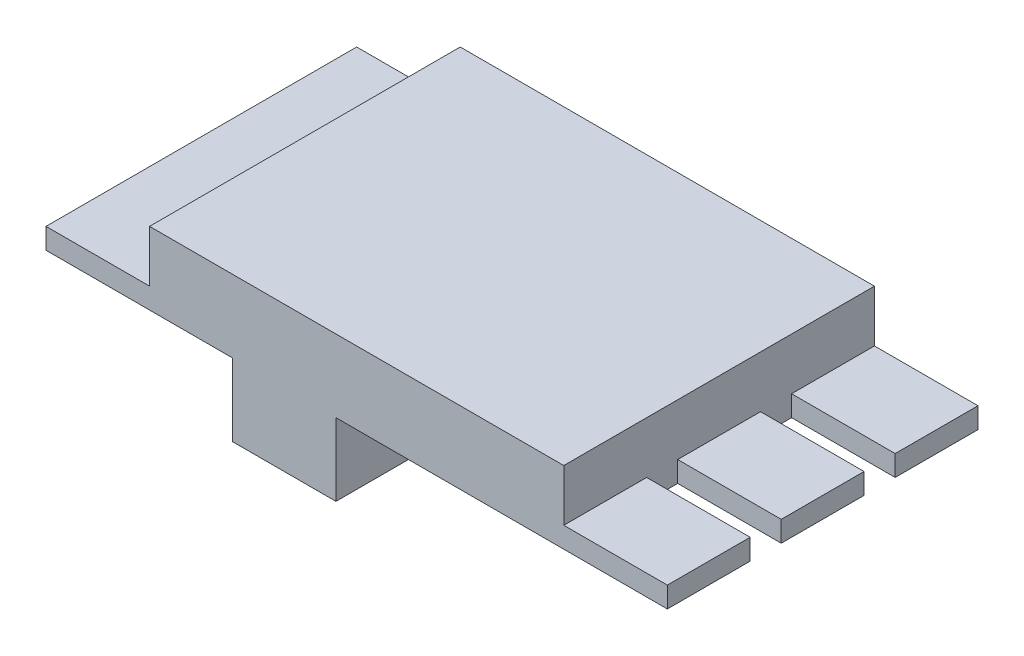
SolidWorks part; units mm, degrees
ref_plane "Front Plane" through (0, 0, 0) normal (0, 0, 1) x (1, 0, 0)
ref_plane "Top Plane" through (0, 0, 0) normal (0, 1, 0) x (1, 0, 0)
ref_plane "Right Plane" through (0, 0, 0) normal (1, 0, 0) x (0, 0, -1)
sketch "Sketch1" plane through (0, 0, 0) normal (0, 1, 0) x (1, 0, 0)
  line L1 (-15, -7.5) -> (15, -7.5)
  line L2 (-15, -7.5) -> (-15, 7.5)
  line L3 (-15, 7.5) -> (15, 7.5)
  line L4 (15, -7.5) -> (15, 7.5)
  line L5 (-15, -7.5) -> (15, 7.5) construction
  line L6 (-15, 7.5) -> (15, -7.5) construction
  point P0 (0, 0)
  dimension "D1" = 30
  dimension "D2" = 15
extrude "Boss-Extrude1" add sketch "Sketch1" along normal blind 7
sketch "Sketch2" plane through (0, 0, 7.5) normal (0, 0, 1) x (1, 0, 0)
  line L0 (15, 4.5) -> (10, 4.5)
  line L1 (15, 7) -> (15, 0) construction
  line L2 (10, 4.5) -> (10, 7)
  line L3 (-15, 7) -> (15, 7) construction
  line L4 (10, 7) -> (-10, 7)
  line L7 (-6, 3.5) -> (-6, 0)
  line L18 (15, 4.5) -> (15, 3.5)
  line L20 (-10, 7) -> (-10, 4.5)
  line L21 (-10, 4.5) -> (-15, 4.5)
  line L22 (-15, 7) -> (-15, 0) construction
  line L23 (-15, 4.5) -> (-15, 3.5)
  line L24 (-15, 3.5) -> (-6, 3.5)
  line L25 (-15, 0) -> (15, 0) construction
  line L26 (-6, 0) -> (-1, 0)
  line L27 (-1, 0) -> (-1, 3.5)
  line L28 (-1, 3.5) -> (15, 3.5)
  dimension "D1" = 5
  dimension "D2" = 20
  dimension "D3" = 5
  dimension "D4" = 1
  dimension "D5" = 16
  dimension "D7" = 1
sketch "Sketch3" plane through (0, 0, 7.5) normal (0, 0, 1) x (1, 0, 0)
  line L1 (-10, 4.5) -> (-15, 4.5)
  line L2 (-10, 4.5) -> (-10, 7)
  line L3 (-10, 7) -> (-15, 7)
  line L4 (-15, 4.5) -> (-15, 7)
  line L5 (-6, 3.5) -> (-15, 3.5)
  line L6 (-6, 3.5) -> (-6, 0)
  line L7 (-6, 0) -> (-15, 0)
  line L8 (-15, 3.5) -> (-15, 0)
  line L13 (10, 4.5) -> (15, 4.5)
  line L14 (10, 4.5) -> (10, 7)
  line L15 (10, 7) -> (15, 7)
  line L16 (15, 4.5) -> (15, 7)
  line L21 (-1, 0) -> (15, 0)
  line L22 (-1, 0) -> (-1, 3.5)
  line L23 (-1, 3.5) -> (15, 3.5)
  line L24 (15, 0) -> (15, 3.5)
extrude "Cut-Extrude1" cut sketch "Sketch3" against normal mid plane 37
sketch "Sketch4" plane through (0, 7, 0) normal (0, 1, 0) x (1, 0, 0)
  line L0 (15, 7.5) -> (15, -7.5) construction
  line L1 (15, 3.5) -> (10, 3.5)
  line L2 (15, 3.5) -> (15, 2)
  line L3 (15, 2) -> (10, 2)
  line L4 (10, 3.5) -> (10, 2)
  line L5 (10, 7.5) -> (10, -7.5) construction
  line L11 (-1000, 0) -> (49000, 0) construction
  line L12 (15, -2) -> (10, -2)
  line L13 (10, -3.5) -> (10, -2)
  line L14 (15, -3.5) -> (10, -3.5)
  line L15 (15, -3.5) -> (15, -2)
  dimension "D1" = 1.5
  dimension "D2" = 2
extrude "Cut-Extrude2" cut sketch "Sketch4" against normal mid plane 37
